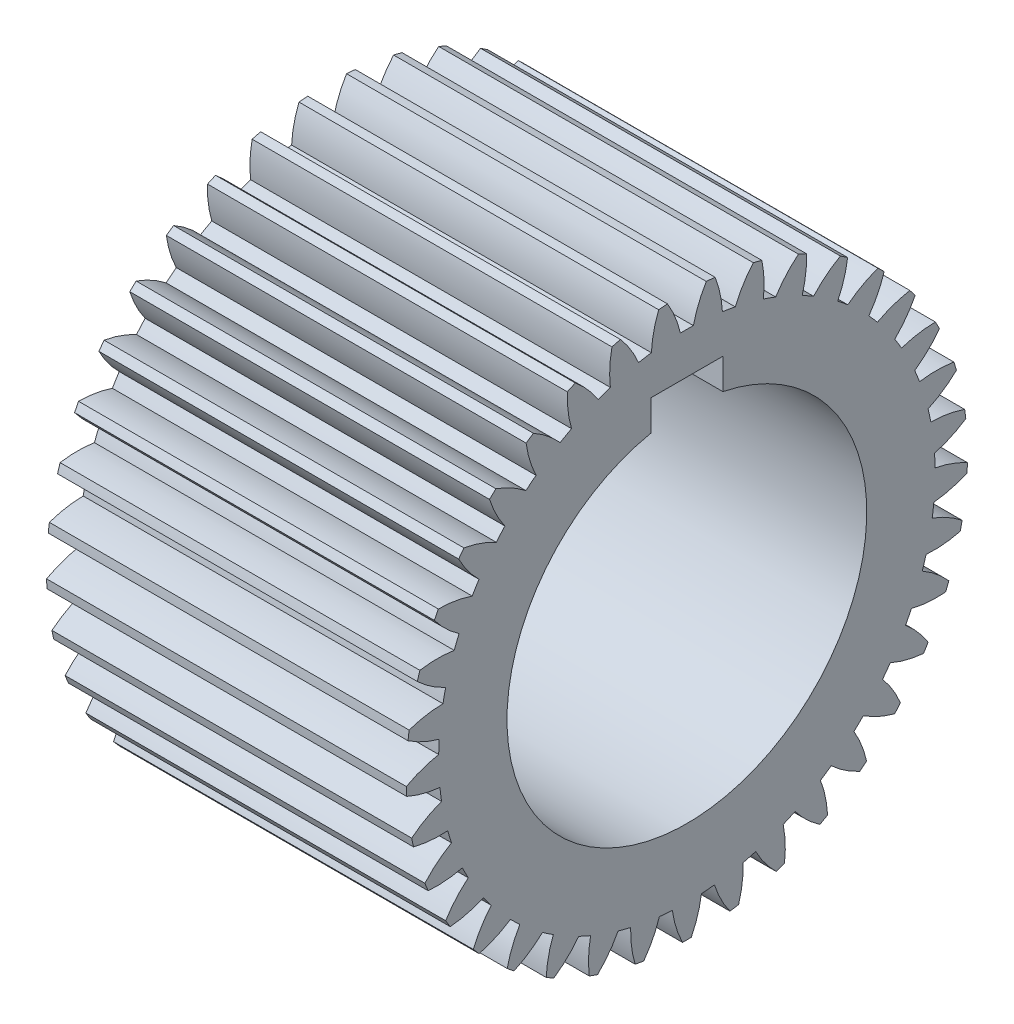
SolidWorks part; units mm, degrees
ref_plane "Plane1" through (0, 0, 0) normal (0, 0, 1) x (1, 0, 0)
ref_plane "Plane2" through (0, 0, 0) normal (0, 1, 0) x (1, 0, 0)
ref_plane "Plane3" through (0, 0, 0) normal (1, 0, 0) x (0, 0, -1)
other "Configuration Table"
sketch "HoldingSke" plane through (0, 0, 0) normal (0, 1, 0) x (1, 0, 0)
  line L0 (0, 0) -> (0.9983, -0.7523)
  line L1 (-15, 0) -> (100, 0) construction
  line L2 (0, 0) -> (-2.1039, 2.3779)
  line L3 (0, 0) -> (-11.863, 4.5341)
  line L4 (0, 0) -> (6.897, 5.1973)
  line L5 (0, 0) -> (-46.8476, -17.4728)
  line L6 (0, 0) -> (-16.5793, -11.1861)
  line L7 (-2.1039, 2.3779) -> (8.6586, 51.2059)
  line L8 (-76.2, 54.61) -> (-73.4, 54.61)
  line L9 (-71.009, 38.7566) -> (-53.1078, 45.2721)
  line L10 (-76.2, 71.12) -> (104.1128, 71.12)
  line L11 (0, 0) -> (-20, 0)
  line L12 (-76.2, 101.6) -> (-76.17, 101.6)
  line L13 (24.9733, 27.94) -> (52.9518, 28.4284)
  line L14 (24.9733, 27.94) -> (24.9743, 27.94)
  line L15 (24.9733, 27.94) -> (100.4006, 29.5858)
  line L16 (-63.627, -0.8) -> (-12.827, -0.8)
  circle A0 centre (0, 0) radius 10
  circle A1 centre (0, 0) radius 13.799
  circle A2 centre (0, 0) radius 37.5
  circle A3 centre (0, 0) radius 10
  dimension "MHD" = 27.598
  dimension "Hub_dia" = 75
  dimension "Bore" = 20
  dimension "MBD" = 20
  dimension "Num_teeth" = 37
  dimension "Pitch" = 1.25
  dimension "Overall_len" = 50
  dimension "Show_teeth" = 37
  dimension "Thickness" = 20
  dimension "OAL" = 50.0001
  dimension "T_dim" = 2.8
  dimension "Ap" = 20
  dimension "H" = 19.05
  dimension "Pitch_radius" = 180.3128
  dimension "Width" = 20
  dimension "Backlash" = 0.03
  dimension "Addendum_fac" = 1
  dimension "Dedendum_fac" = 1.25
  dimension "Clearance_fac" = 0.25
  dimension "Dedendum_add" = 0.001
  dimension "Module" = 0.8
sketch "BasProSke" plane through (0, 0, 0) normal (0, 1, 0) x (1, 0, 0)
  line L0 (-10, 0) -> (60, 0) construction
  line L1 (0, 0) -> (0, 15.6)
  line L2 (0, 0) -> (20, 0)
  line L3 (20, 0) -> (20, 15.6)
  line L4 (20, 15.6) -> (0, 15.6)
  dimension "Thickness" = 20
  dimension "Diameter" = 31.2
revolve "Base-Revolve" add sketch "BasProSke" angle 360 about L0
sketch "TooCutSke" plane through (0, 0, 0) normal (1, 0, 0) x (0, 0, -1)
  line L1 (0, 0) -> (0, 107) construction
  line L2 (0, 0) -> (-0.6806, 14.7843) construction
  line L3 (0, 0) -> (-2.5084, 29.471) construction
  line L4 (-0.6806, 14.7843) -> (-1.2542, 14.7355) construction
  arc A0 (0.3617, 13.7943) -> (-0.3617, 13.7943) centre (0, 0) ccw
  arc A1 (1.0943, 15.587) -> (-1.0943, 15.587) centre (0, 0) ccw
  circle A2 centre (0, 0) radius 14.8 construction
  circle A3 centre (0, 0) radius 13.9075 construction
  arc A4 (-0.3617, 13.7943) -> (-1.0943, 15.587) centre (-6.1344, 12.4815) ccw
  arc A5 (1.0943, 15.587) -> (0.3617, 13.7943) centre (6.1344, 12.4815) ccw
  dimension "Root_dia" = 27.598
  dimension "Overcut_dia" = 31.2508
  dimension "Pitch_dia" = 29.6
  dimension "Base_dia" = 27.8149
  dimension "Flank_rad" = 5.92
  dimension "Half_ang" = 4.865
  dimension "Half_CT" = 0.5756
extrude "ToothCut" cut sketch "TooCutSke" along normal through all
fillet "Breaks" [suppressed] radius 0.016
fillet "RootFillets" [suppressed] radius 0.201
pattern_circular "TeethCuts" count 37 every 9.73 about axis through (-10, 0, 0) along (1, 0, 0) of "ToothCut", "RootFillets", "Breaks"
sketch "HubNeaOneSke" plane through (0, 0, 0) normal (-1, 0, 0) x (0, 0, 1)
  circle A0 centre (0, 0) radius 13.799
  dimension "Diameter" = 27.598
extrude "HubNearOne" [suppressed] add sketch "HubNeaOneSke" along normal blind 30.0001
sketch "HubNeaBotSke" plane through (0, 0, 0) normal (-1, 0, 0) x (0, 0, 1)
  circle A0 centre (0, 0) radius 13.799
  dimension "Diameter" = 27.598
extrude "HubNearBoth" [suppressed] add sketch "HubNeaBotSke" along normal blind 15
ref_plane "FarPln" through (20, 0, 0) normal (1, 0, 0) x (0, 0, -1)
sketch "HubFarSke" plane through (20, 0, 0) normal (1, 0, 0) x (0, 0, -1)
  circle A0 centre (0, 0) radius 13.799
  dimension "Diameter" = 27.598
extrude "HubFar" [suppressed] add sketch "HubFarSke" along normal blind 15
sketch "BorSke" plane through (0, 0, 0) normal (1, 0, 0) x (0, 0, -1)
  circle A0 centre (0, 0) radius 10
  dimension "Diameter" = 20
extrude "Bore" cut sketch "BorSke" along normal mid plane 100.0001
sketch "KeySke" plane through (0, 0, 0) normal (1, 0, 0) x (0, 0, -1)
  line L0 (-2, 0) -> (2, 0)
  line L1 (-2, 0) -> (-2, 11.5)
  line L2 (2, 0) -> (2, 11.5)
  line L3 (0, 0) -> (0, 34) construction
  line L4 (2, 11.5) -> (-2, 11.5)
  point P3 (0, 0)
extrude "Keyway" cut sketch "KeySke" along normal mid plane 100.0001
pattern_circular "Keyway2" [suppressed] count 2 every 90 about axis through (-10, 0, 0) along (1, 0, 0)
equation "' \"Module@HoldingSke\" = 6.35"
equation "' \"Num_teeth@HoldingSke\" = 12"
equation "' \"Ap@HoldingSke\" =  20"
equation "' \"Ap@HoldingSke\" = 20"
equation "' \"Width@HoldingSke\" = 0.5 * 25.4"
equation "' \"Hub_dia@HoldingSke\"= 1 * 25.4"
equation "' \"Hub_dia@HoldingSke\" = 1 * 25.4"
equation "' \"Overall_len@HoldingSke\" = 1.0 * 25.4"
equation "' \"Bore@HoldingSke\" = 0.75 * 25.4"
equation "' \"T_dim@HoldingSke\" = 0.1 * 25.4"
equation "' \"Width@KeySke\" = 0.25 * 25.4"
equation "' \"Show_teeth@HoldingSke\" = 13"
equation "' \"Backlash@HoldingSke\" = 0.009 * 25.4"
equation "' \"Addendum_fac@HoldingSke\" = 1.0"
equation "' \"Dedendum_fac@HoldingSke\" = 1.25"
equation "' \"Dedendum_add@HoldingSke\" = 0.00005 * 25.4"
equation "' \"Clearance_fac@HoldingSke\" = 0.25"
equation "\"Pitch@HoldingSke\" = 1 / \"Module@HoldingSke\""
equation "\"Overcut_dia@TooCutSke\" = (\"Num_teeth@HoldingSke\" + 2 * \"Addendum_fac@HoldingSke\") / \"Pitch@HoldingSke\" + 0.002 * 25.4"
equation "\"Pitch_dia@TooCutSke\" = \"Num_teeth@HoldingSke\" / \"Pitch@HoldingSke\""
equation "\"Base_dia@TooCutSke\" = \"Num_teeth@HoldingSke\" / \"Pitch@HoldingSke\" * cos((\"Ap@HoldingSke\"  * 3.14159265 / 180))"
equation "\"Root_dia@TooCutSke\" = (\"Num_teeth@HoldingSke\" + 2) / \"Pitch@HoldingSke\" - 2 * (\"Addendum_fac@HoldingSke\" + \"Dedendum_fac@HoldingSke\") / \"Pitch@HoldingSke\" - \"Dedendum_add@HoldingSke\" * 2"
equation "\"Half_ang@TooCutSke\" = 180 / \"Num_teeth@HoldingSke\""
equation "\"Half_CT@TooCutSke\" = \"Num_teeth@HoldingSke\" / \"Pitch@HoldingSke\" * sin((3.14159265 / 2 / \"Num_teeth@HoldingSke\")) / 2 - 7 * \"Backlash@HoldingSke\" / 4"
equation "\"Flank_rad@TooCutSke\" = \"Num_teeth@HoldingSke\" / \"Pitch@HoldingSke\" / 5"
equation "\"Radius@RootFillets\" = \"Clearance_fac@HoldingSke\" / \"Pitch@HoldingSke\" + \"Dedendum_add@HoldingSke\""
equation "\"Break_rad@Breaks\" = 0.02 / \"Pitch@HoldingSke\""
equation "\"Thickness@HoldingSke\" = \"Width@HoldingSke\""
equation "\"OAL@HoldingSke\" = \"Thickness@HoldingSke\""
equation "\"MHD@HoldingSke\" = (\"Num_teeth@HoldingSke\" + 2) / \"Pitch@HoldingSke\" - 2 * (\"Addendum_fac@HoldingSke\" + \"Dedendum_fac@HoldingSke\")  / \"Pitch@HoldingSke\" - \"Dedendum_add@HoldingSke\" * 2"
equation "\"MBD@HoldingSke\" = (\"Num_teeth@HoldingSke\" + 2) / \"Pitch@HoldingSke\" - 2 * (\"Addendum_fac@HoldingSke\" + \"Dedendum_fac@HoldingSke\")  / \"Pitch@HoldingSke\" - \"Dedendum_add@HoldingSke\" * 2 - 0.002 * 25.4"
equation "\"MHD@HoldingSke\" = ((sgn( \"MHD@HoldingSke\" - \"Hub_dia@HoldingSke\" )-1)*( \"MHD@HoldingSke\" - \"Hub_dia@HoldingSke\" ))/-2+ \"Hub_dia@HoldingSke\""
equation "\"MBD@HoldingSke\" = ((sgn( \"MBD@HoldingSke\" - \"Bore@HoldingSke\" )-1)*( \"MBD@HoldingSke\" - \"Bore@HoldingSke\" ))/-2+ \"Bore@HoldingSke\""
equation "\"OAL@HoldingSke\" = ((sgn( \"OAL@HoldingSke\" - \"Overall_len@HoldingSke\" )+1)*( \"OAL@HoldingSke\" - \"Overall_len@HoldingSke\" ))/2 + \"Overall_len@HoldingSke\" + 0.000002 * 25.4"
equation "\"Num_teeth@TeethCuts\" = int( \"Show_teeth@HoldingSke\" ) + 1"
equation "\"Num_teeth@TeethCuts\" = ((sgn( \"Num_teeth@TeethCuts\" - \"Num_teeth@HoldingSke\" )-1)*( \"Num_teeth@TeethCuts\" - \"Num_teeth@HoldingSke\" ))/-2+ \"Num_teeth@HoldingSke\""
equation "\"Num_teeth@TeethCuts\" = ((sgn( \"Num_teeth@TeethCuts\" - 2.0)+1)*( \"Num_teeth@TeethCuts\" - 2.0))/2 +2.0"
equation "\"Angle@TeethCuts\" = 360.0 / \"Num_teeth@HoldingSke\""
equation "\"Diameter@BasProSke\" = (\"Num_teeth@HoldingSke\" + 2 * \"Addendum_fac@HoldingSke\") / \"Pitch@HoldingSke\""
equation "\"Thickness@BasProSke\"  = \"Thickness@HoldingSke\""
equation "' \"Fillet_rad@BasProSke\" =  \"Thickness@HoldingSke\" * 0.05"
equation "' \"Fillet_rad@BasProSke\" = \"Thickness@HoldingSke\" * 0.05"
equation "\"MHD@HoldingSke\" = ((sgn( \"MHD@HoldingSke\" - \"Root_dia@TooCutSke\" )-1)*( \"MHD@HoldingSke\" - \"Root_dia@TooCutSke\" ))/-2+ \"Root_dia@TooCutSke\""
equation "\"Diameter@HubNeaOneSke\" = \"MHD@HoldingSke\""
equation "\"Length@HubNearOne\" = \"OAL@HoldingSke\" - \"Thickness@BasProSke\""
equation "\"Diameter@HubNeaBotSke\" = \"MHD@HoldingSke\""
equation "\"Length@HubNearBoth\" = ( \"OAL@HoldingSke\" - \"Thickness@BasProSke\" ) / 2.0"
equation "\"Thickness@FarPln\" = \"Thickness@BasProSke\""
equation "\"Diameter@HubFarSke\" = \"MHD@HoldingSke\""
equation "\"Length@HubFar\" = ( \"OAL@HoldingSke\" - \"Thickness@BasProSke\" ) / 2.0"
equation "\"Diameter@BorSke\" = \"MBD@HoldingSke\""
equation "\"D1@Bore\" = \"OAL@HoldingSke\" * 2.0"
equation "\"D1@Keyway\" = \"OAL@HoldingSke\" * 2.0"
